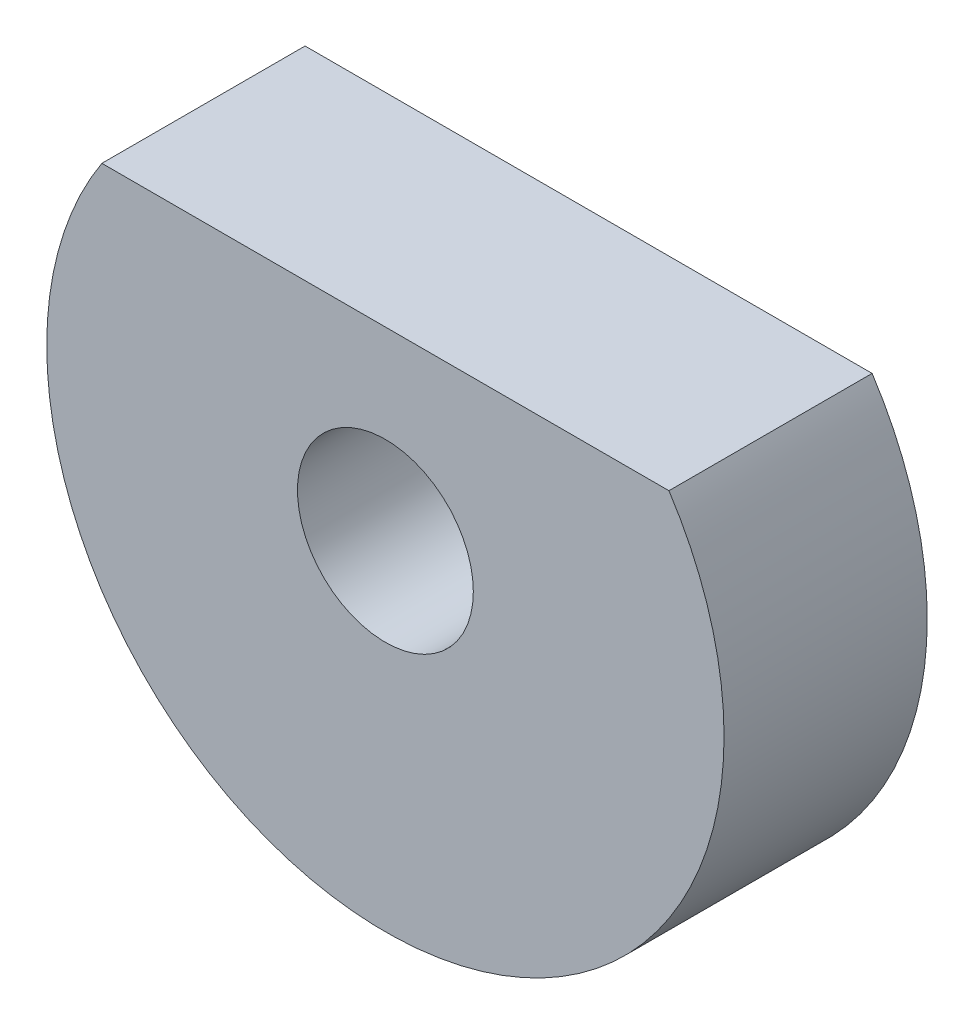
SolidWorks part; units mm, degrees
ref_plane "Front Plane" through (0, 0, 0) normal (0, 0, 1) x (1, 0, 0)
ref_plane "Top Plane" through (0, 0, 0) normal (0, 1, 0) x (1, 0, 0)
ref_plane "Right Plane" through (0, 0, 0) normal (1, 0, 0) x (0, 0, -1)
sketch "Sketch1" plane through (0, 0, 0) normal (0, 0, 1) x (1, 0, 0)
  line L0 (-2.093, 1.3672) -> (2.093, 1.3672)
  arc A0 (-2.093, 1.3672) -> (2.093, 1.3672) centre (0, 0) ccw
  circle A1 centre (0, 0) radius 0.6491
  dimension "D1" = 5
extrude "Boss-Extrude1" add sketch "Sketch1" along normal blind 1.5
